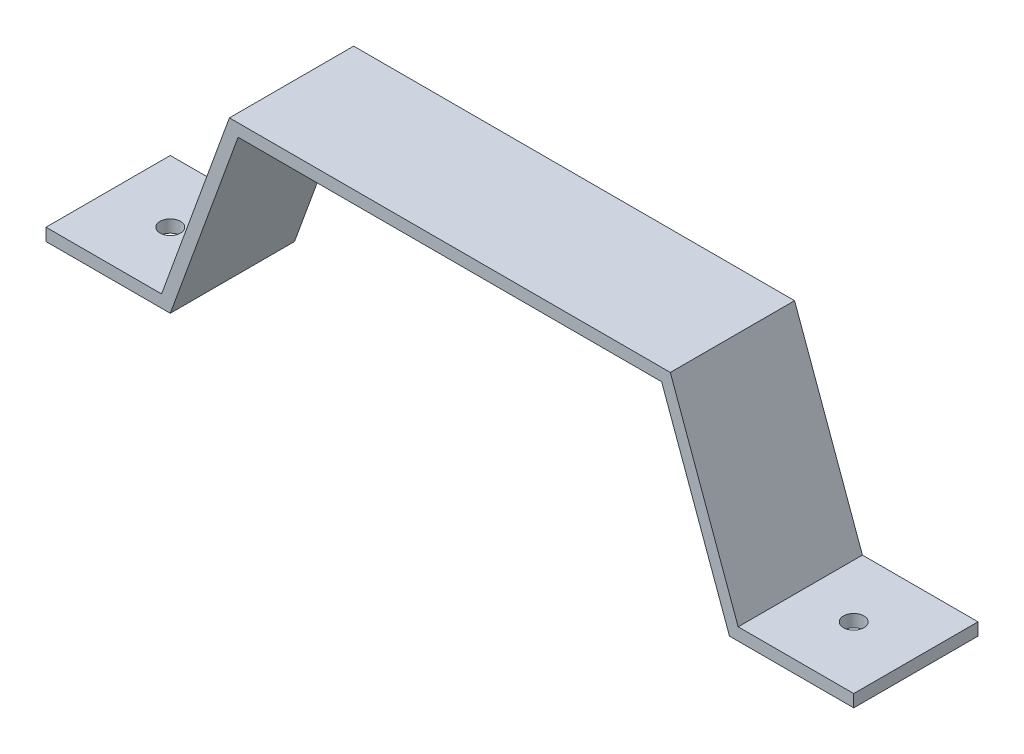
SolidWorks part; units mm, degrees
ref_plane "前视基准面" through (0, 0, 0) normal (0, 0, 1) x (1, 0, 0)
ref_plane "上视基准面" through (0, 0, 0) normal (0, 1, 0) x (1, 0, 0)
ref_plane "右视基准面" through (0, 0, 0) normal (1, 0, 0) x (0, 0, -1)
other "Configuration Table"
sketch "草图1" plane through (0, 0, 0) normal (0, 0, 1) x (1, 0, 0)
  line L0 (-71.3521, 0) -> (-51.3521, 0)
  line L1 (-51.3521, 0) -> (-40.433, 30)
  line L2 (-40.433, 30) -> (27.7288, 30)
  line L4 (29.1292, 32) -> (-41.8334, 32)
  line L5 (-41.8334, 32) -> (-52.7525, 2)
  line L6 (-52.7525, 2) -> (-71.3521, 2)
  line L7 (-71.3521, 2) -> (-71.3521, 0)
  line L8 (58.6479, 2) -> (58.6479, 0)
  line L9 (40.0483, 2) -> (58.6479, 2)
  line L10 (29.1292, 32) -> (40.0483, 2)
  line L11 (38.6479, 0) -> (27.7288, 30)
  line L12 (58.6479, 0) -> (38.6479, 0)
  dimension "D1" = 20
  dimension "D2" = 110
  dimension "D3" = 2
  dimension "D4" = 2
  dimension "D5" = 20
  dimension "D6" = 30
  dimension "D7" = 90
  dimension "D8" = 110
  dimension "D9" = 110
  dimension "D10" = 2
  dimension "D11" = 2
  dimension "D12" = 2
extrude "凸台-拉伸1" add sketch "草图1" along normal blind 20
sketch "草图2" plane through (0, 0, 0) normal (0, 1, 0) x (1, 0, 0)
  line L0 (-71.3521, -10) -> (58.6479, -10) construction
  line L1 (-71.3521, -20) -> (-71.3521, 0) construction
  line L2 (58.6479, -20) -> (58.6479, 0) construction
  line L3 (-6.3521, 0) -> (-6.3521, -20) construction
  line L4 (29.1292, 0) -> (-41.8334, 0) construction
  line L5 (29.1292, -20) -> (-41.8334, -20) construction
  line L6 (-71.3521, -10) -> (58.6479, -10) construction
  circle A2 centre (-61.3521, -10) radius 1.6451
  circle A3 centre (48.6479, -10) radius 1.6451
  dimension "D1" = 10
  dimension "D3" = 0
extrude "切除-拉伸1" cut sketch "草图2" along normal blind 20
